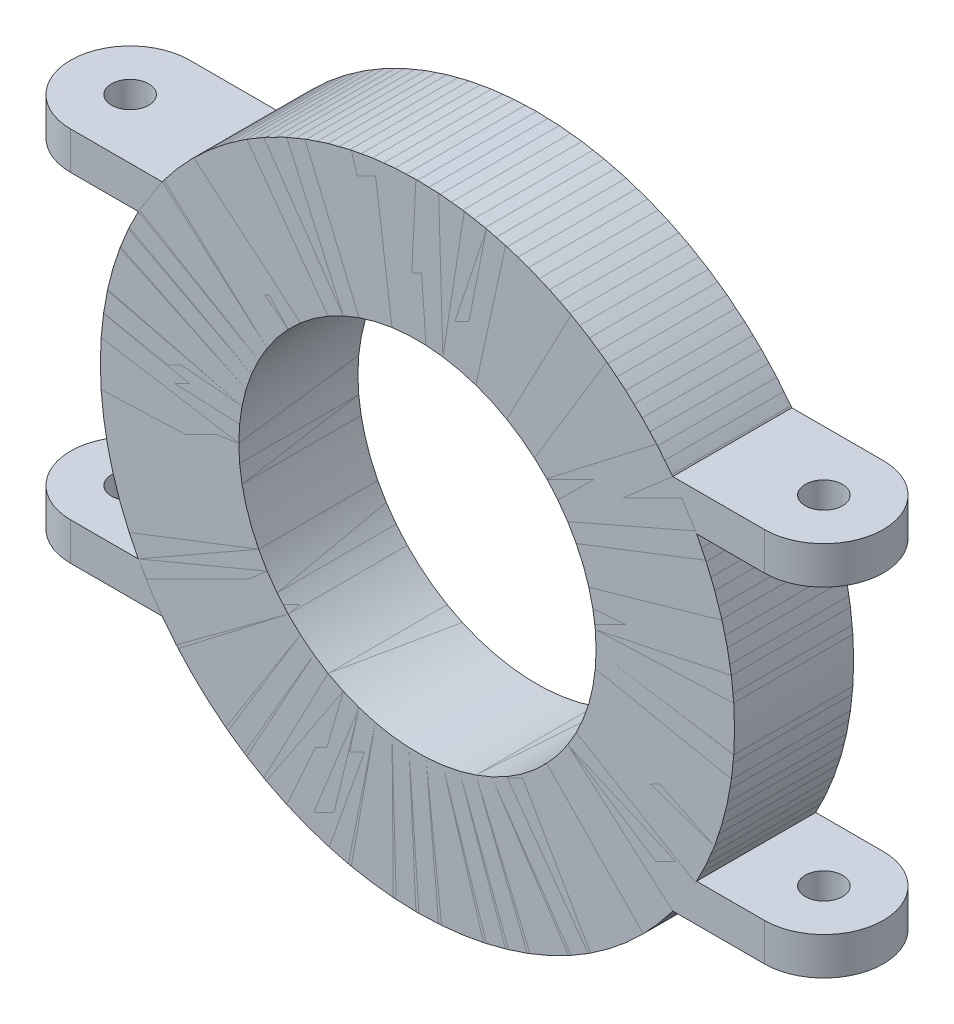
SolidWorks part; units mm, degrees
material "ABS"
ref_plane "Front Plane" through (0, 0, 0) normal (0, 0, 1) x (1, 0, 0)
ref_plane "Top Plane" through (0, 0, 0) normal (0, 1, 0) x (1, 0, 0)
ref_plane "Right Plane" through (0, 0, 0) normal (1, 0, 0) x (0, 0, -1)
sketch "Sketch2" plane through (0, 0, 0) normal (0, 0, 1) x (1, 0, 0)
  line L0 (0, 0) -> (21.3, 0)
  circle A0 centre (0, 0) radius 21.3
  circle A1 centre (0, 0) radius 12
extrude "Boss-Extrude1" add sketch "Sketch2" along normal blind 8
ref_plane "Plane1" through (21.3, 0, 0) normal (1, 0, 0) x (0, 0, -1)
ref_plane "Plane2" through (16.3, 0, 0) normal (1, 0, 0) x (0, 0, -1)
sketch "Sketch3" plane through (16.3, 0, 0) normal (1, 0, 0) x (0, 0, -1)
  line L0 (0, 0) -> (-8, 0)
  line L1 (-8, 21.3) -> (-8, -21.3) construction
  line L3 (0, 12) -> (0, -12) construction
  line L4 (-8, 12.6354) -> (0, 12.6354)
  line L5 (-8, 12.6354) -> (-8, 10.1039)
  line L6 (-8, 10.1039) -> (0, 10.1039)
  line L7 (0, 12.6354) -> (0, 10.1039)
  line L8 (-8, 12.6354) -> (0, 10.1039) construction
  line L9 (-8, 10.1039) -> (0, 12.6354) construction
  line L10 (-8, -12.6354) -> (-8, -10.1039)
  line L11 (0, -12.6354) -> (0, -10.1039)
  line L12 (-8, -10.1039) -> (0, -10.1039)
  line L13 (-8, -12.6354) -> (0, -12.6354)
  line L14 (-4, 10.1039) -> (-4, -13.4891)
  point P8 (-4, 0)
extrude "Boss-Extrude2" add sketch "Sketch3" along normal blind 7
ref_plane "Plane3" through (23.3, 0, 0) normal (1, 0, 0) x (0, 0, -1)
sketch "Sketch4" plane through (23.3, 0, 0) normal (1, 0, 0) x (0, 0, -1)
  line L0 (-8, 10.1039) -> (0, 10.1039) construction
  line L1 (-4, 10.1039) -> (0, 10.1039)
  line L2 (-4, 10.1039) -> (-4, 12.6354)
  line L3 (-4, 12.6354) -> (0, 12.6354)
  line L4 (0, 10.1039) -> (0, 12.6354)
revolve "Revolve1" add sketch "Sketch4" angle 360 about L2
sketch "Sketch5" plane through (23.3, 0, 0) normal (1, 0, 0) x (0, 0, -1)
  line L0 (-8, -12.6354) -> (0, -12.6354) construction
  line L1 (-4, -12.6354) -> (0, -12.6354)
  line L2 (-4, -12.6354) -> (-4, -10.1039)
  line L3 (-4, -10.1039) -> (0, -10.1039)
  line L4 (0, -12.6354) -> (0, -10.1039)
revolve "Revolve2" add sketch "Sketch5" angle 360 about L2
ref_plane "Plane4" through (0, -12.6354, 0) normal (0, -1, 0) x (-1, 0, 0)
sketch "Sketch6" plane through (0, -12.6354, 0) normal (0, -1, 0) x (-1, 0, 0)
  circle A0 centre (-23.3, -4) radius 1.25
extrude "Cut-Extrude1" cut sketch "Sketch6" against normal up to surface (25.2707 mm away) up to face at (21.2238, 12.6354, 4)
pattern_circular "CirPattern2" count 2 over 360 about axis through (0, 0, 0) along (0, 0, 1) of bodies 106
ref_plane "Plane5" through (0, 0, 8) normal (0, 0, 1) x (1, 0, 0)
sketch "Sketch7" plane through (0, 0, 8) normal (0, 0, 1) x (1, 0, 0)
  circle A0 centre (0, 0) radius 21.3
